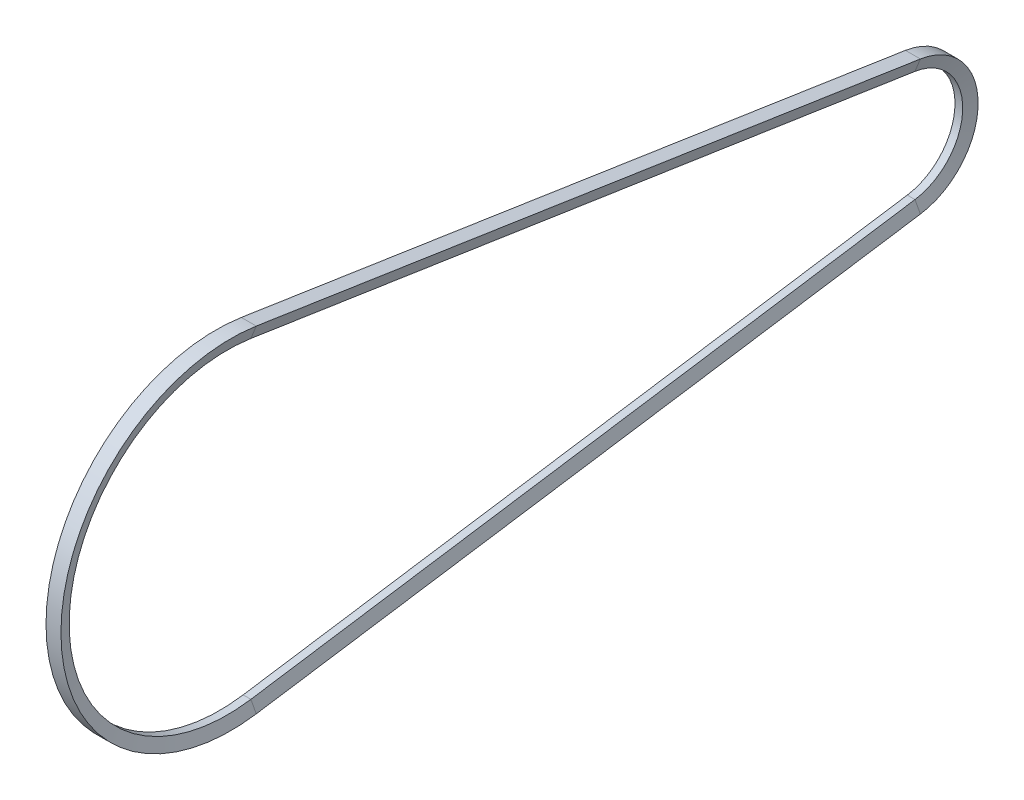
SolidWorks part; units mm, degrees
ref_plane "前视基准面" through (0, 0, 0) normal (0, 0, 1) x (1, 0, 0)
ref_plane "上视基准面" through (0, 0, 0) normal (0, 1, 0) x (1, 0, 0)
ref_plane "右视基准面" through (0, 0, 0) normal (1, 0, 0) x (0, 0, -1)
sketch "草图1" plane through (0, 0, 0) normal (1, 0, 0) x (0, 0, -1)
  line L0 (18.75, 123.5857) -> (507.5, 49.4343)
  line L1 (18.75, -123.5857) -> (507.5, -49.4343)
  line L2 (0, 0) -> (500, 0) construction
  arc A0 (18.75, 123.5857) -> (18.75, -123.5857) centre (0, 0) ccw
  arc A1 (507.5, -49.4343) -> (507.5, 49.4343) centre (500, 0) ccw
  dimension "D1" = 125
  dimension "D2" = 50
  dimension "D3" = 500
sketch "草图2" plane through (0, 0, 0) normal (0, 0, 1) x (1, 0, 0)
  line L0 (-5.5, 125) -> (5.5, 125)
  line L1 (5.5, 125) -> (2.8401, 116.3)
  line L2 (2.8401, 116.3) -> (-2.8401, 116.3)
  line L3 (-2.8401, 116.3) -> (-5.5, 125)
  line L4 (0, 116.3) -> (0, 125) construction
  line L5 (0, -125) -> (0, 125) construction
  dimension "D1" = 11
  dimension "D2" = 8.7
  dimension "D3" = 34
sweep "扫描1" add profiles "草图2" path "草图1"
equation "\"D3@草图1\" = \"D1@距离1@实心轮_孔板轮.Assembly\""
equation "\"D1@草图2\" = \"bd@草图1@小带轮_实心轮.Part\" "
equation "\"D2@草图2\" = \"hf@草图1@大带轮_孔板轮.Part\" "
equation "\"D3@草图2\" = \"槽轮角@草图1@大带轮_孔板轮.Part\" "
equation "\"D2@草图1\" = \"dd@草图1@小带轮_实心轮.Part\"/2"
equation "\"D1@草图1\" = \"dd@草图1@大带轮_孔板轮.Part\" /2"
